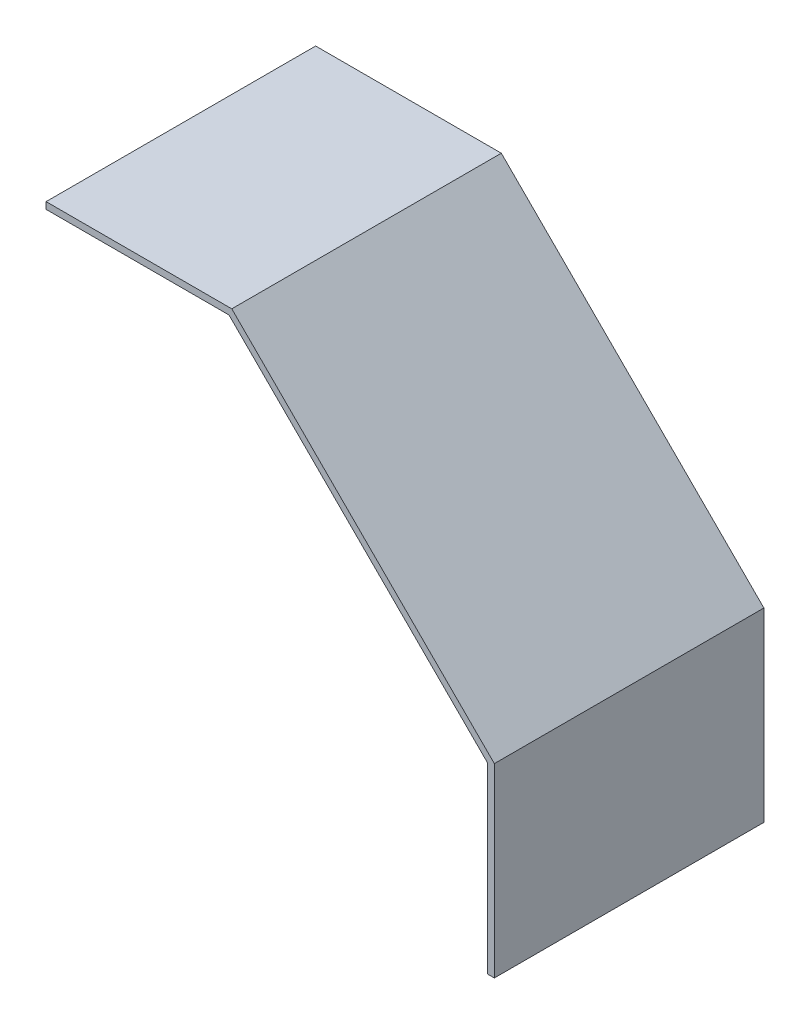
SolidWorks part; units mm, degrees
ref_plane "Front Plane" through (0, 0, 0) normal (0, 0, 1) x (1, 0, 0)
ref_plane "Top Plane" through (0, 0, 0) normal (0, 1, 0) x (1, 0, 0)
ref_plane "Right Plane" through (0, 0, 0) normal (1, 0, 0) x (0, 0, -1)
sketch "Sketch1" plane through (0, 0, 0) normal (0, 0, 1) x (1, 0, 0)
  line L0 (422.3977, 174.9629) -> (422.3977, 0) construction
  line L1 (174.9629, 422.3977) -> (422.3977, 174.9629) construction
  line L2 (0, 422.3977) -> (174.9629, 422.3977) construction
  line L3 (422.3977, 174.9629) -> (422.3977, 0)
  line L4 (174.9629, 422.3977) -> (422.3977, 174.9629)
  line L5 (0, 422.3977) -> (174.9629, 422.3977)
extrude "Extrude-Thin1" add sketch "Sketch1" along normal blind 254 thin
